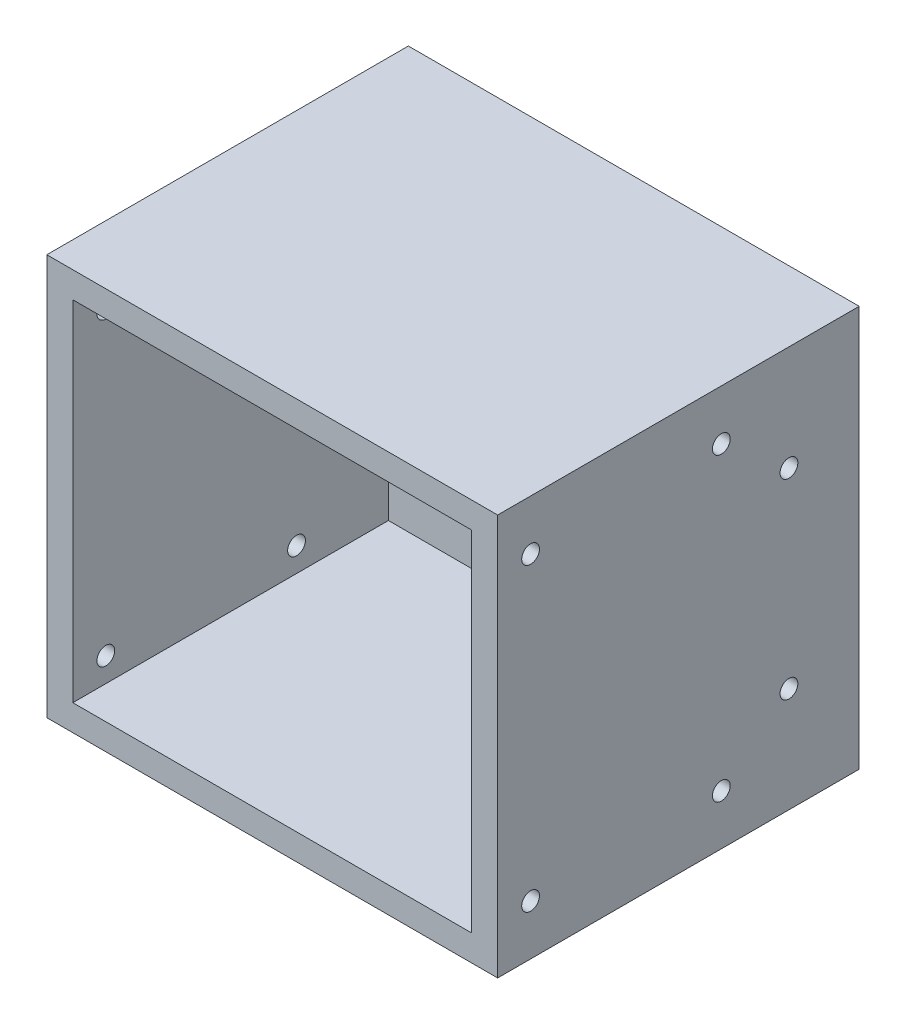
SolidWorks part; units mm, degrees
ref_plane "Plano frontal" through (0, 0, 0) normal (0, 0, 1) x (1, 0, 0)
ref_plane "Plano superior" through (0, 0, 0) normal (0, 1, 0) x (1, 0, 0)
ref_plane "Plano direito" through (0, 0, 0) normal (1, 0, 0) x (0, 0, -1)
sketch "Esboço1" plane through (0, 0, 0) normal (0, 0, 1) x (1, 0, 0)
  line L1 (-23, -20.125) -> (23, -20.125)
  line L2 (-23, -20.125) -> (-23, 20.125)
  line L3 (-23, 20.125) -> (23, 20.125)
  line L4 (23, -20.125) -> (23, 20.125)
  line L5 (-23, -20.125) -> (23, 20.125) construction
  line L6 (-23, 20.125) -> (23, -20.125) construction
  circle A1 centre (0, 0) radius 14
  point P0 (0, 0)
extrude "Ressalto-extrusão1" add sketch "Esboço1" against normal blind 5.3
ref_plane "Plano1" through (-23, 0, 0) normal (-1, 0, 0) x (0, 0, 1)
sketch "Esboço2" plane through (-23, 0, 0) normal (-1, 0, 0) x (0, 0, 1)
  line L0 (-5.3, -20.125) -> (-5.3, 20.125)
  line L1 (-5.3, -20.125) -> (36.4, -20.125)
  line L2 (-5.3, 20.125) -> (36.4, 20.125)
  line L3 (36.4, -20.125) -> (36.4, 20.125)
  line L4 (0, 20.125) -> (0, -20.125) construction
  line L5 (0, 0) -> (39.5906, 0) construction
  circle A0 centre (32.6, 17.325) radius 1.025
  circle A1 centre (10.6, 17.325) radius 1.025
  circle A2 centre (10.6, -17.325) radius 1.025
  circle A3 centre (32.6, -17.325) radius 1.025
  circle A4 centre (2.8, 11.025) radius 1.025
  circle A5 centre (2.8, -11.025) radius 1.025
  dimension "D1" = 2.8
  dimension "D4" = 7.8
  dimension "D5" = 6.3
  dimension "D6" = 2.8
  dimension "D2" = 32.6
  dimension "D3" = 2
extrude "Ressalto-extrusão2" add sketch "Esboço2" along normal blind 3
ref_plane "Plano2" through (0, 20.125, 0) normal (0, 1, 0) x (1, 0, 0)
sketch "Esboço3" plane through (0, 20.125, 0) normal (0, 1, 0) x (1, 0, 0)
  line L4 (-26, 5.3) -> (-26, -36.4)
  line L5 (-26, 5.3) -> (23, 5.3)
  line L6 (-26, -36.4) -> (23, -36.4)
  line L7 (23, 5.3) -> (23, -36.4)
extrude "Ressalto-extrusão3" add sketch "Esboço3" along normal blind 3
ref_plane "Plano3" through (23, 0, 0) normal (1, 0, 0) x (0, 0, -1)
sketch "Esboço4" plane through (23, 0, 0) normal (1, 0, 0) x (0, 0, -1)
  line L0 (-36.4, 23.125) -> (5.3, 23.125)
  line L1 (-36.4, 23.125) -> (-36.4, -20.125)
  line L2 (5.3, 23.125) -> (5.3, -20.125)
  line L3 (-36.4, -20.125) -> (5.3, -20.125)
extrude "Ressalto-extrusão4" add sketch "Esboço4" along normal blind 3
ref_plane "Plano5" through (0, -20.125, 0) normal (0, -1, 0) x (-1, 0, 0)
sketch "Esboço5" plane through (0, -20.125, 0) normal (0, -1, 0) x (-1, 0, 0)
  line L0 (26, -36.4) -> (-26, -36.4)
  line L1 (26, -36.4) -> (26, 5.3)
  line L2 (-26, -36.4) -> (-26, 5.3)
  line L3 (26, 5.3) -> (-26, 5.3)
extrude "Ressalto-extrusão5" add sketch "Esboço5" along normal blind 3
sketch "Esboço7" plane through (-23, 0, 0) normal (-1, 0, 0) x (0, 0, 1)
  circle A0 centre (2.8, 11.025) radius 1.025
  circle A1 centre (10.6, 17.325) radius 1.025
  circle A2 centre (32.6, 17.325) radius 1.025
  circle A3 centre (2.8, -11.025) radius 1.025
  circle A4 centre (10.6, -17.325) radius 1.025
  circle A5 centre (32.6, -17.325) radius 1.025
extrude "Corte-extrusão1" cut sketch "Esboço7" against normal through all both and the other way through all
